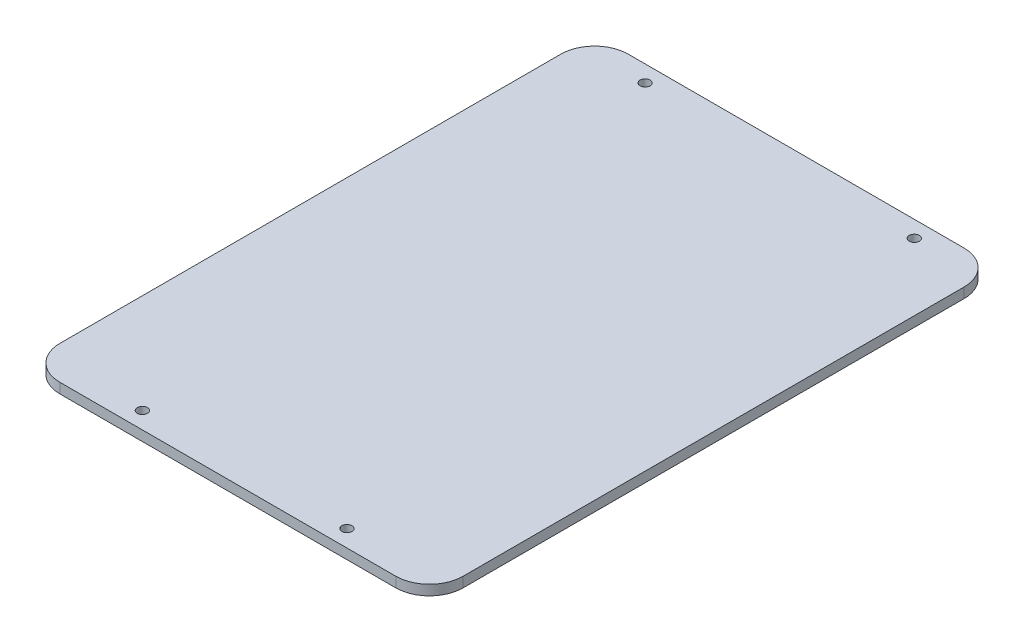
SolidWorks part; units mm, degrees
ref_plane "Front Plane" through (0, 0, 0) normal (0, 0, 1) x (1, 0, 0)
ref_plane "Top Plane" through (0, 0, 0) normal (0, 1, 0) x (1, 0, 0)
ref_plane "Right Plane" through (0, 0, 0) normal (1, 0, 0) x (0, 0, -1)
sketch "Sketch1" plane through (0, 0, 0) normal (0, 1, 0) x (1, 0, 0)
  line L0 (59.85, 168.7) -> (59.85, 0) construction
  line L1 (10, 0) -> (109.7, 0)
  line L2 (0, 10) -> (0, 158.7)
  line L3 (10, 168.7) -> (109.7, 168.7)
  line L4 (119.7, 10) -> (119.7, 158.7)
  circle A0 centre (19.9, 163.81) radius 1.5
  circle A1 centre (29.49, 4.99) radius 1.5
  circle A2 centre (90.21, 4.99) radius 1.5
  circle A3 centre (99.8, 163.81) radius 1.5
  arc A4 (109.7, 0) -> (119.7, 10) centre (109.7, 10) ccw
  arc A5 (10, 0) -> (0, 10) centre (10, 10) cw
  arc A6 (109.7, 168.7) -> (119.7, 158.7) centre (109.7, 158.7) cw
  arc A7 (0, 158.7) -> (10, 168.7) centre (10, 158.7) cw
  point P17 (119.7, 0)
  point P20 (0, 0)
  point P23 (119.7, 168.7)
  dimension "D3" = 3
  dimension "D4" = 3
  dimension "D5" = 4.89
  dimension "D9" = 10
  dimension "D1" = 168.7
  dimension "D2" = 119.7
  dimension "D6" = 39.95
  dimension "D7" = 4.99
  dimension "D8" = 30.36
extrude "Boss-Extrude1" add sketch "Sketch1" along normal blind 3
